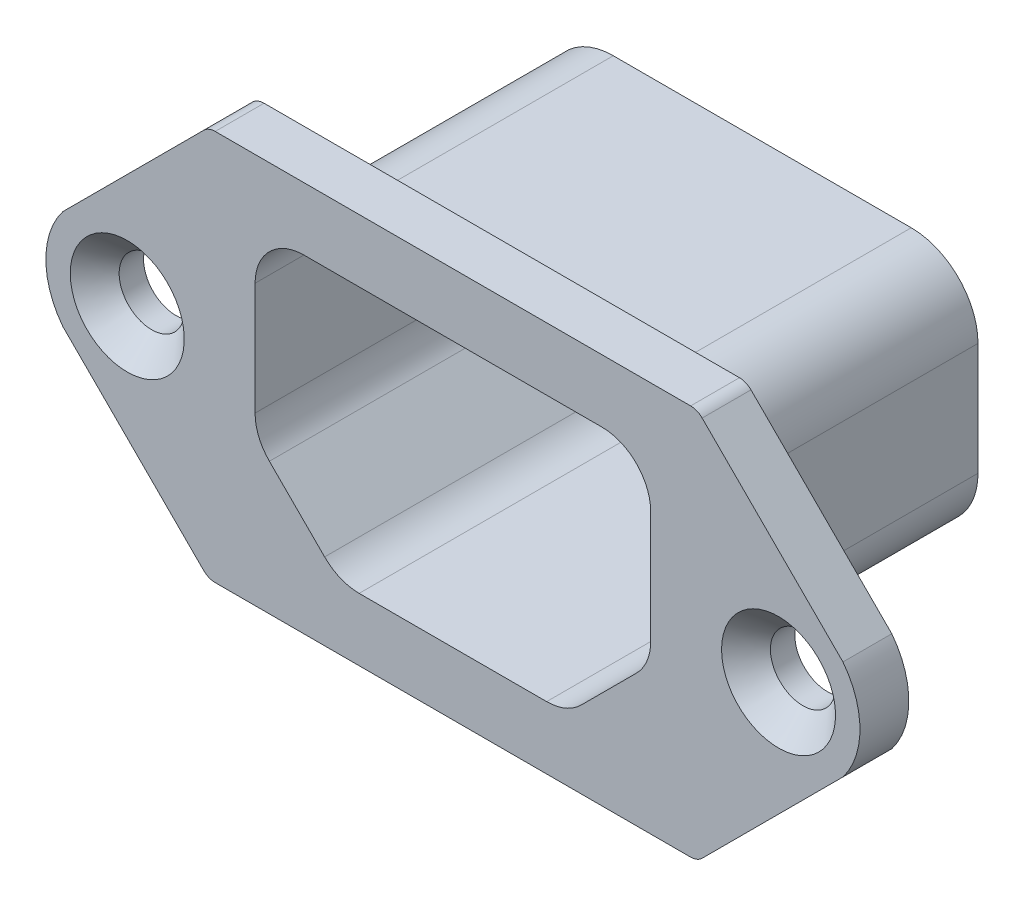
SolidWorks part; units mm, degrees
ref_plane "Front Plane" through (0, 0, 0) normal (0, 0, 1) x (1, 0, 0)
ref_plane "Top Plane" through (0, 0, 0) normal (0, 1, 0) x (1, 0, 0)
ref_plane "Right Plane" through (0, 0, 0) normal (1, 0, 0) x (0, 0, -1)
sketch "Sketch2" plane through (0, 0, 0) normal (0, 0, 1) x (1, 0, 0)
  line L0 (0, 337.9268) -> (0, -314.0732) construction
  line L1 (-605.2866, 0) -> (582.4268, 0) construction
  line L2 (-11.2713, -3.8787) -> (-7.8787, -7.2713)
  line L3 (5.7574, -8.15) -> (-5.7574, -8.15)
  line L4 (12.15, -1.7574) -> (12.15, 5.15)
  line L5 (9.15, 8.15) -> (-9.15, 8.15)
  line L6 (-12.15, -1.7574) -> (-12.15, 5.15)
  line L7 (9.0676, -6.0824) -> (-12.15, 8.15) construction
  line L8 (12.15, 8.15) -> (-9.0676, -6.0824) construction
  line L9 (11.2713, -3.8787) -> (7.8787, -7.2713)
  line L10 (-15.3071, 11.7071) -> (-23.9545, 3.0597)
  line L11 (14.6, -12) -> (-14.6, -12)
  line L13 (14.6, 12) -> (-14.6, 12)
  line L15 (15.6, -12) -> (-15.6, 12) construction
  line L16 (15.6, 12) -> (-15.6, -12) construction
  line L17 (-15.3071, -11.7071) -> (-23.9545, -3.0597)
  line L18 (15.3071, -11.7071) -> (23.9545, -3.0597)
  line L19 (15.3071, 11.7071) -> (23.9545, 3.0597)
  arc A0 (9.15, 8.15) -> (12.15, 5.15) centre (9.15, 5.15) cw
  arc A1 (-9.15, 8.15) -> (-12.15, 5.15) centre (-9.15, 5.15) ccw
  arc A2 (12.15, -1.7574) -> (11.2713, -3.8787) centre (9.15, -1.7574) cw
  arc A3 (7.8787, -7.2713) -> (5.7574, -8.15) centre (5.7574, -5.15) cw
  arc A4 (-12.15, -1.7574) -> (-11.2713, -3.8787) centre (-9.15, -1.7574) ccw
  arc A5 (-7.8787, -7.2713) -> (-5.7574, -8.15) centre (-5.7574, -5.15) ccw
  arc A6 (14.6, 12) -> (15.3071, 11.7071) centre (14.6, 11) cw
  arc A7 (-15.3071, 11.7071) -> (-14.6, 12) centre (-14.6, 11) cw
  arc A8 (15.3071, -11.7071) -> (14.6, -12) centre (14.6, -11) cw
  arc A9 (-14.6, -12) -> (-15.3071, -11.7071) centre (-14.6, -11) cw
  circle A10 centre (-20, 0) radius 2
  arc A11 (-23.9545, -3.0597) -> (-23.9545, 3.0597) centre (-20, 0) cw
  circle A12 centre (20, 0) radius 2
  arc A13 (23.9545, -3.0597) -> (23.9545, 3.0597) centre (20, 0) ccw
  point P5 (0, 0)
  point P22 (12.15, -3)
  point P25 (7, -8.15)
  point P28 (-12.15, -3)
  point P31 (-7, -8.15)
  point P32 (0, 0)
  point P54 (-25, 0)
  dimension "D9" = 3
  dimension "D10" = 3
  dimension "D13" = 1
  dimension "D14" = 4
  dimension "D18" = 5
  dimension "D1" = 11.15
  dimension "D2" = 16.3
  dimension "D3" = 7
  dimension "D4" = 45
  dimension "D5" = 24.3
  dimension "D6" = 14
  dimension "D7" = 7.2832
  dimension "D8" = 5.15
  dimension "D11" = 24
  dimension "D12" = 31.2
  dimension "D15" = 40
  dimension "D17" = 24
extrude "Boss-Extrude1" add sketch "Sketch2" along normal mid plane 3
sketch "Sketch3" plane through (0, 0, -1.5) normal (0, 0, -1) x (-1, 0, 0)
  line L0 (12.15, 5.15) -> (12.15, -1.7574) construction
  line L1 (11.2713, -3.8787) -> (7.8787, -7.2713) construction
  line L2 (5.7574, -8.15) -> (-5.7574, -8.15) construction
  line L3 (-7.8787, -7.2713) -> (-11.2713, -3.8787) construction
  line L4 (-9.15, 8.15) -> (9.15, 8.15) construction
  line L5 (-12.15, -1.7574) -> (-12.15, 5.15) construction
  line L6 (12.15, 5.15) -> (12.15, -1.7574)
  line L7 (11.2713, -3.8787) -> (7.8787, -7.2713)
  line L8 (5.7574, -8.15) -> (-5.7574, -8.15)
  line L9 (-7.8787, -7.2713) -> (-11.2713, -3.8787)
  line L10 (-9.15, 8.15) -> (9.15, 8.15)
  line L11 (-12.15, -1.7574) -> (-12.15, 5.15)
  line L12 (-9.15, 9.25) -> (9.15, 9.25)
  line L13 (-13.25, -1.7574) -> (-13.25, 5.15)
  line L14 (-8.6565, -8.0491) -> (-12.0491, -4.6565)
  line L15 (5.7574, -9.25) -> (-5.7574, -9.25)
  line L16 (12.0491, -4.6565) -> (8.6565, -8.0491)
  line L17 (13.25, 5.15) -> (13.25, -1.7574)
  arc A0 (12.15, 5.15) -> (9.15, 8.15) centre (9.15, 5.15) ccw construction
  arc A1 (11.2713, -3.8787) -> (12.15, -1.7574) centre (9.15, -1.7574) ccw construction
  arc A2 (5.7574, -8.15) -> (7.8787, -7.2713) centre (5.7574, -5.15) ccw construction
  arc A3 (-7.8787, -7.2713) -> (-5.7574, -8.15) centre (-5.7574, -5.15) ccw construction
  arc A4 (-9.15, 8.15) -> (-12.15, 5.15) centre (-9.15, 5.15) ccw construction
  arc A5 (-12.15, -1.7574) -> (-11.2713, -3.8787) centre (-9.15, -1.7574) ccw construction
  arc A6 (12.15, 5.15) -> (9.15, 8.15) centre (9.15, 5.15) ccw
  arc A7 (11.2713, -3.8787) -> (12.15, -1.7574) centre (9.15, -1.7574) ccw
  arc A8 (5.7574, -8.15) -> (7.8787, -7.2713) centre (5.7574, -5.15) ccw
  arc A9 (-7.8787, -7.2713) -> (-5.7574, -8.15) centre (-5.7574, -5.15) ccw
  arc A10 (-9.15, 8.15) -> (-12.15, 5.15) centre (-9.15, 5.15) ccw
  arc A11 (-12.15, -1.7574) -> (-11.2713, -3.8787) centre (-9.15, -1.7574) ccw
  arc A12 (13.25, 5.15) -> (9.15, 9.25) centre (9.15, 5.15) ccw
  arc A13 (-9.15, 9.25) -> (-13.25, 5.15) centre (-9.15, 5.15) ccw
  arc A14 (-13.25, -1.7574) -> (-12.0491, -4.6565) centre (-9.15, -1.7574) ccw
  arc A15 (-8.6565, -8.0491) -> (-5.7574, -9.25) centre (-5.7574, -5.15) ccw
  arc A16 (5.7574, -9.25) -> (8.6565, -8.0491) centre (5.7574, -5.15) ccw
  arc A17 (12.0491, -4.6565) -> (13.25, -1.7574) centre (9.15, -1.7574) ccw
  dimension "D2" = 18.5
  dimension "D1" = 1.1
extrude "Boss-Extrude2" add sketch "Sketch3" along normal blind 16
sketch "Sketch4" plane through (0, 0, -17.5) normal (0, 0, -1) x (-1, 0, 0)
  line L6 (9.15, 9.25) -> (-9.15, 9.25)
  line L7 (-13.25, 5.15) -> (-13.25, -1.7574)
  line L8 (-12.0491, -4.6565) -> (-8.6565, -8.0491)
  line L9 (-5.7574, -9.25) -> (5.7574, -9.25)
  line L10 (8.6565, -8.0491) -> (12.0491, -4.6565)
  line L11 (13.25, -1.7574) -> (13.25, 5.15)
  line L12 (9.15, 9.25) -> (-9.15, 9.25)
  line L13 (-13.25, 5.15) -> (-13.25, -1.7574)
  line L14 (-12.0491, -4.6565) -> (-8.6565, -8.0491)
  line L15 (-5.7574, -9.25) -> (5.7574, -9.25)
  line L16 (8.6565, -8.0491) -> (12.0491, -4.6565)
  line L17 (13.25, -1.7574) -> (13.25, 5.15)
  arc A6 (13.25, 5.15) -> (9.15, 9.25) centre (9.15, 5.15) ccw
  arc A7 (-9.15, 9.25) -> (-13.25, 5.15) centre (-9.15, 5.15) ccw
  arc A8 (-13.25, -1.7574) -> (-12.0491, -4.6565) centre (-9.15, -1.7574) ccw
  arc A9 (-8.6565, -8.0491) -> (-5.7574, -9.25) centre (-5.7574, -5.15) ccw
  arc A10 (5.7574, -9.25) -> (8.6565, -8.0491) centre (5.7574, -5.15) ccw
  arc A11 (12.0491, -4.6565) -> (13.25, -1.7574) centre (9.15, -1.7574) ccw
  arc A12 (13.25, 5.15) -> (9.15, 9.25) centre (9.15, 5.15) ccw
  arc A13 (-9.15, 9.25) -> (-13.25, 5.15) centre (-9.15, 5.15) ccw
  arc A14 (-13.25, -1.7574) -> (-12.0491, -4.6565) centre (-9.15, -1.7574) ccw
  arc A15 (-8.6565, -8.0491) -> (-5.7574, -9.25) centre (-5.7574, -5.15) ccw
  arc A16 (5.7574, -9.25) -> (8.6565, -8.0491) centre (5.7574, -5.15) ccw
  arc A17 (12.0491, -4.6565) -> (13.25, -1.7574) centre (9.15, -1.7574) ccw
  dimension "D1" = 0
extrude "Boss-Extrude3" add sketch "Sketch4" against normal blind 1
chamfer "Chamfer1" distance 1.5 angle 45 2 edges at (18, 0, 1.5) (-18, 0, 1.5)
